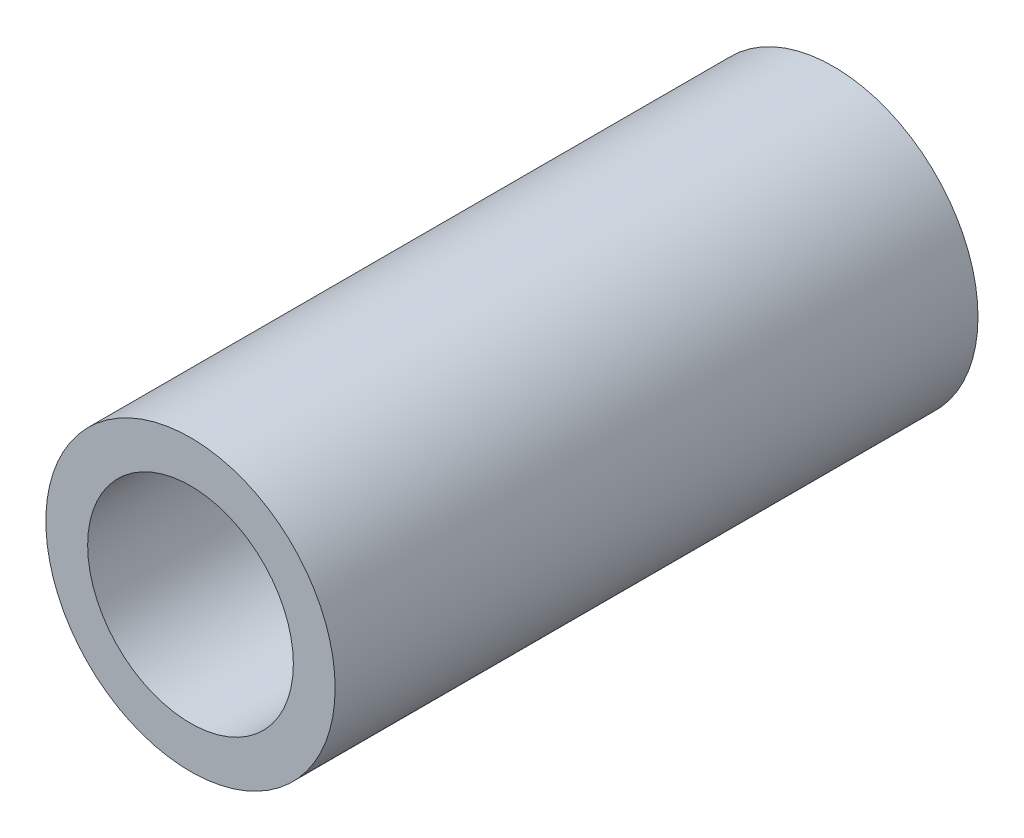
SolidWorks part; units mm, degrees
ref_plane "Front Plane" through (0, 0, 0) normal (0, 0, 1) x (1, 0, 0)
ref_plane "Top Plane" through (0, 0, 0) normal (0, 1, 0) x (1, 0, 0)
ref_plane "Right Plane" through (0, 0, 0) normal (1, 0, 0) x (0, 0, -1)
sketch "Sketch1" plane through (0, 0, 0) normal (0, 0, 1) x (1, 0, 0)
  circle A0 centre (0, 0) radius 2.25
  circle A1 centre (0, 0) radius 1.6
  dimension "OD" = 4.5
  dimension "ID" = 3.2
extrude "Extrude1" add sketch "Sketch1" along normal mid plane 10
sketch "Sketch2" plane through (0, 0, 0) normal (1, 0, 0) x (0, 0, -1)
  line L0 (-5, -1.6) -> (5, -1.6) construction
  line L3 (5, 1.6) -> (-5, 1.6) construction
  line L5 (-5, -1.6) -> (5, -1.6)
  line L6 (5, 1.6) -> (-5, 1.6)
sketch "Sketch4" plane through (0, 0, 5) normal (0, 0, 1) x (1, 0, 0)
  line L0 (0, 0) -> (-1.1314, 1.1314)
  line L1 (0, -1.1) -> (0, 1.1) construction
  circle A0 centre (0, 0) radius 1.6 construction
  dimension "D1" = 45
